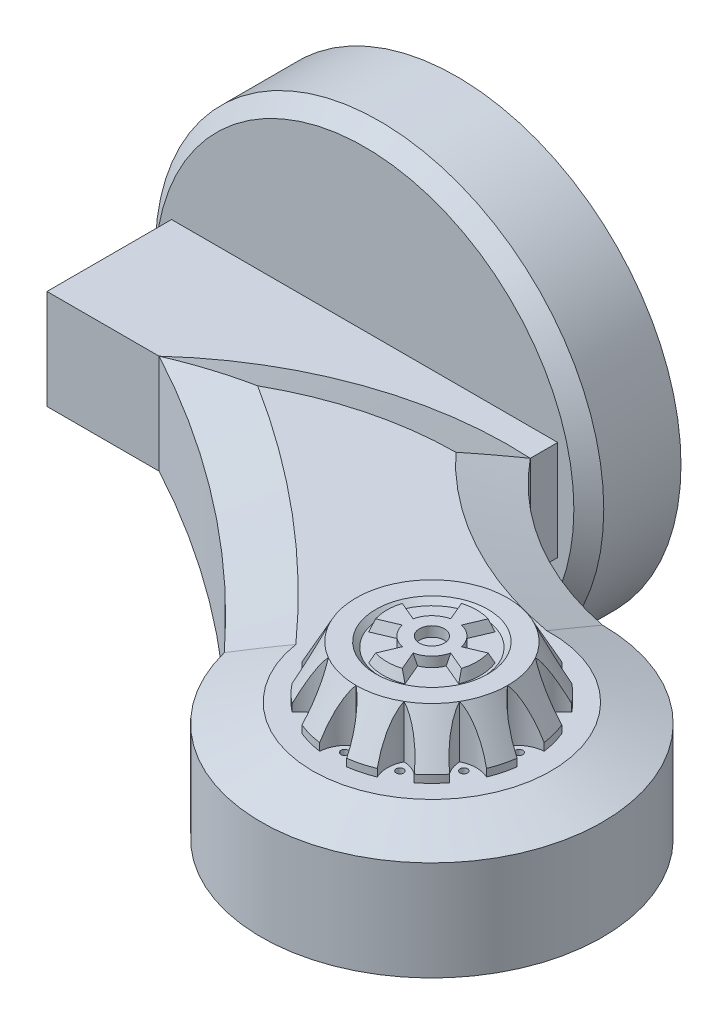
SolidWorks part; units mm, degrees
ref_plane "Front Plane" through (0, 0, 0) normal (1, 0, 0) x (0, 1, 0)
ref_plane "Top Plane" through (0, 0, 0) normal (0, 0, 1) x (0, 1, 0)
ref_plane "Right Plane" through (0, 0, 0) normal (0, 1, 0) x (-1, 0, 0)
sketch "Sketch1" plane through (0, 0, 0) normal (0, 0, 1) x (0, 1, 0)
  circle A0 centre (0, 0) radius 90
  dimension "D1" = 180
extrude "Boss-Extrude1" add sketch "Sketch1" along normal blind 37
chamfer "Chamfer1" distance 6 angle 45 1 edges at (90, 0, 37)
sketch "Sketch2" plane through (0, 0, 37) normal (0, 0, 1) x (1, 0, 0)
  line L1 (77.5, 20) -> (-77.5, 20)
  line L2 (77.5, 20) -> (77.5, -20)
  line L3 (77.5, -20) -> (-77.5, -20)
  line L4 (-77.5, 20) -> (-77.5, -20)
  line L5 (77.5, 20) -> (-77.5, -20) construction
  line L6 (77.5, -20) -> (-77.5, 20) construction
  point P0 (0, 0)
  dimension "D1" = 155
  dimension "D2" = 40
extrude "Boss-Extrude2" add sketch "Sketch2" along normal blind 50 contours L2 L1 L4 L3
sketch "Sketch3" plane through (0, 20, 0) normal (0, 1, 0) x (-1, 0, 0)
  line L0 (-77.5, 87) -> (32.5, 87)
  line L1 (-77.5, 87) -> (77.5, 87) construction
  line L2 (-77.5, 87) -> (-77.5, 48)
  line L3 (-77.5, 87) -> (-77.5, 37) construction
  arc A0 (-77.5, 48) -> (32.5, 87) centre (-68.6761, 197.7402) ccw
  dimension "D3" = 150
  dimension "D1" = 39
  dimension "D2" = 110
extrude "Cut-Extrude1" cut sketch "Sketch3" against normal through all
sketch "Sketch5" plane through (0, 0, 0) normal (0, 1, 0) x (-1, 0, 0)
  arc A0 (-83.6314, 176.9548) -> (-150, 91.5) centre (-150, 160) ccw
  arc A1 (-150, 91.5) -> (-77.5, 48) centre (-174.2724, -31.1207) cw
  arc A2 (32.5, 87) -> (-83.6314, 176.9548) centre (240.0972, 474.9477) cw
  arc A3 (-77.5, 48) -> (32.5, 87) centre (-68.6761, 197.7402) ccw construction
  arc A4 (-77.5, 48) -> (32.5, 87) centre (-68.6761, 197.7402) ccw
  dimension "D3" = 137
  dimension "D4" = 440
  dimension "D5" = 125
  dimension "D1" = 150
  dimension "D2" = 160
extrude "Boss-Extrude3" add sketch "Sketch5" along normal mid plane 40 separate body contours A0 A1 A4 A2
sketch "Sketch7" plane through (0, 20, 0) normal (0, 1, 0) x (-1, 0, 0)
  arc A4 (-83.6314, 176.9548) -> (32.5, 87) centre (240.0972, 474.9477) ccw
  arc A5 (-83.6314, 176.9548) -> (-150, 91.5) centre (-150, 160) ccw
  arc A6 (-77.5, 48) -> (-150, 91.5) centre (-174.2724, -31.1207) ccw
  arc A7 (-77.5, 48) -> (32.5, 87) centre (-68.6761, 197.7402) ccw
  arc A8 (-83.6314, 176.9548) -> (32.5, 87) centre (240.0972, 474.9477) ccw
  arc A9 (-83.6314, 176.9548) -> (-150, 91.5) centre (-150, 160) ccw
  arc A10 (-77.5, 48) -> (-150, 91.5) centre (-174.2724, -31.1207) ccw
  arc A11 (-77.5, 48) -> (32.5, 87) centre (-68.6761, 197.7402) ccw
  dimension "D1" = 0
extrude "Boss-Extrude4" add sketch "Sketch7" along normal blind 7.5 draft 70 contours A8 A11 A10 A9
sketch "Sketch8" plane through (0, 27.5, 0) normal (0, 1, 0) x (-1, 0, 0)
  circle A0 centre (-150, 160) radius 40
  dimension "D1" = 80
extrude "Boss-Extrude5" add sketch "Sketch8" along normal blind 3 contours A0
sketch "Sketch9" plane through (0, 30.5, 0) normal (0, 1, 0) x (-1, 0, 0)
  circle A1 centre (-150, 160) radius 40
  circle A2 centre (-150, 160) radius 40
  dimension "D1" = 0
extrude "Boss-Extrude6" add sketch "Sketch9" along normal blind 18 draft 28 contours A2
sketch "Sketch10" plane through (0, 48.5, 0) normal (0, 1, 0) x (-1, 0, 0)
  line L0 (-150, 160) -> (-150, 410.856) construction
  circle A0 centre (-150, 160) radius 40 construction
  arc A1 (-144.5652, 199.6291) -> (-155.4348, 199.6291) centre (-150, 160) ccw
  arc A4 (-150, 190.4292) -> (-144.5652, 199.6291) centre (-156.5339, 200.4944) ccw
  arc A5 (-150, 190.4292) -> (-155.4348, 199.6291) centre (-143.4661, 200.4944) cw
  dimension "D1" = 12
extrude "Cut-Extrude2" cut sketch "Sketch10" against normal up to surface (21 mm away) up to face at (150, 27.5, 200)
sketch "Sketch11" plane through (0, 27.5, 0) normal (0, 1, 0) x (-1, 0, 0)
  line L0 (-155.4348, 199.6291) -> (-144.5652, 199.6291) construction
  line L1 (-150, 190.4292) -> (-150, 199.6291) construction
  circle A0 centre (-150, 195.0291) radius 1.5
  dimension "D1" = 3
extrude "Cut-Extrude3" cut sketch "Sketch11" against normal blind 5 contours A0
pattern_circular "CirPattern1" count 12 over 360 about axis through (150, 0, 160) along (0, 1, 0) of "Cut-Extrude2", "Cut-Extrude3"
sketch "Sketch12" plane through (0, 48.5, 0) normal (0, 1, 0) x (-1, 0, 0)
  circle A0 centre (-150, 160) radius 22.5
  dimension "D1" = 45
extrude "Cut-Extrude4" cut sketch "Sketch12" against normal blind 2 draft 45
sketch "Sketch13" plane through (0, 46.5, 0) normal (0, 1, 0) x (-1, 0, 0)
  line L0 (-150, 160) -> (-150, 222.5263) construction
  line L1 (-153, 167.953) -> (-157.2996, 178.0822)
  line L2 (-147, 167.953) -> (-142.7004, 178.0822)
  arc A0 (-147, 167.953) -> (-153, 167.953) centre (-150, 160) ccw
  arc A1 (-142.7004, 178.0822) -> (-157.2996, 178.0822) centre (-150, 160) ccw
  dimension "D1" = 17
  dimension "D2" = 39
  dimension "D4" = 3
  dimension "D3" = 23
extrude "Boss-Extrude7" add sketch "Sketch13" along normal blind 4 draft 20
pattern_circular "CirPattern2" count 4 over 360 about axis through (150, 0, 160) along (0, 1, 0) of "Boss-Extrude7"
sketch "Sketch14" plane through (0, 46.5, 0) normal (0, 1, 0) x (-1, 0, 0)
  circle A0 centre (-150, 160) radius 9.9559
extrude "Boss-Extrude8" add sketch "Sketch14" along normal up to surface (4 mm away) up to face at (150, 50.5, 173.737)
sketch "Sketch15" plane through (0, 50.5, 0) normal (0, 1, 0) x (-1, 0, 0)
  circle A0 centre (-150, 160) radius 5
  dimension "D1" = 10
extrude "Cut-Extrude5" cut sketch "Sketch15" against normal up to surface (4 mm away) up to face at (150, 46.5, 180.5)
sketch "Sketch16" plane through (0, -20, 0) normal (0, -1, 0) x (1, 0, 0)
  circle A0 centre (150, 160) radius 15
  dimension "D1" = 30
extrude "Cut-Extrude6" cut sketch "Sketch16" against normal blind 20
sketch "Sketch17" plane through (0, 0, 0) normal (0, 0, -1) x (1, 0, 0)
  circle A0 centre (0, 0) radius 15
  dimension "D1" = 30
extrude "Cut-Extrude7" cut sketch "Sketch17" against normal blind 20 contours A0
